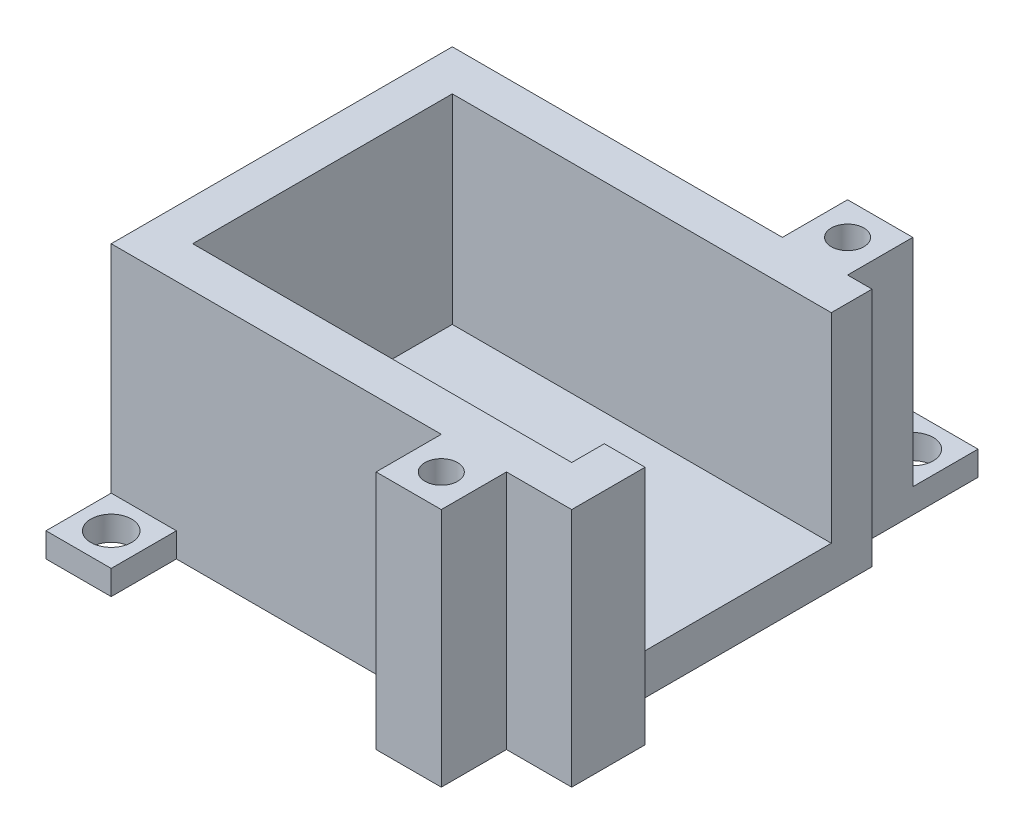
SolidWorks part; units mm, degrees
ref_plane "Front Plane" through (0, 0, 0) normal (0, 0, 1) x (1, 0, 0)
ref_plane "Top Plane" through (0, 0, 0) normal (0, 1, 0) x (1, 0, 0)
ref_plane "Right Plane" through (0, 0, 0) normal (1, 0, 0) x (0, 0, -1)
sketch "Sketch1" plane through (0, 0, 0) normal (0, 1, 0) x (1, 0, 0)
  line L17 (0, 0) -> (51.5, 0)
  line L18 (51.5, 0) -> (51.5, -5)
  line L19 (51.5, -5) -> (5, -5)
  line L20 (5, -5) -> (5, -36.85)
  line L21 (5, -36.85) -> (51.5, -36.85)
  line L22 (51.5, -36.85) -> (51.5, -32.85)
  line L23 (51.5, -32.85) -> (56.5, -32.85)
  line L24 (56.5, -32.85) -> (56.5, -41.85)
  line L25 (56.5, -41.85) -> (0, -41.85)
  line L26 (0, -41.85) -> (0, 0)
  dimension "D1" = 31.85
  dimension "D2" = 5
  dimension "D3" = 5
  dimension "D4" = 5
  dimension "D5" = 5
  dimension "D6" = 51.5
  dimension "D7" = 56.5
  dimension "D8" = 4
extrude "Boss-Extrude1" add sketch "Sketch1" along normal blind 24.5
sketch "Sketch2" plane through (0, 0, 0) normal (0, -1, 0) x (1, 0, 0)
  line L1 (0, 41.85) -> (103, 41.85)
  line L2 (0, 41.85) -> (0, 0)
  line L3 (0, 0) -> (103, 0)
  line L4 (103, 41.85) -> (103, 0)
  dimension "D1" = 103
extrude "Boss-Extrude2" add sketch "Sketch2" along normal blind 5
sketch "Sketch3" plane through (0, 0, 0) normal (0, 1, 0) x (1, 0, 0)
  line L0 (56.5, -32.85) -> (51.5, -32.85) construction
  line L1 (51.5, -5) -> (98, -5)
  line L2 (51.5, -5) -> (51.5, -32.85)
  line L3 (51.5, -32.85) -> (98, -32.85)
  line L4 (98, -5) -> (98, -32.85)
  line L6 (103, 0) -> (103, -41.85) construction
  dimension "D1" = 0
  dimension "D2" = 5
extrude "Cut-Extrude1" cut sketch "Sketch3" against normal blind 26
sketch "Sketch4" plane through (0, 0, 41.85) normal (0, 0, 1) x (1, 0, 0)
  line L1 (0, -5) -> (8, -5)
  line L2 (0, -5) -> (0, -2)
  line L3 (0, -2) -> (8, -2)
  line L4 (8, -5) -> (8, -2)
  dimension "D1" = 3
  dimension "D2" = 8
sketch "Sketch7" plane through (0, 0, 41.85) normal (0, 0, 1) x (1, 0, 0)
  line L1 (0, -2) -> (8, -2)
  line L2 (0, -2) -> (0, -5)
  line L3 (0, -5) -> (8, -5)
  line L4 (8, -2) -> (8, -5)
extrude "Boss-Extrude3" add sketch "Sketch7" along normal blind 8
sketch "Sketch8" plane through (0, -2, 0) normal (0, 1, 0) x (1, 0, 0)
  line L0 (8, -49.85) -> (8, -41.85) construction
  line L1 (0, -41.85) -> (8, -41.85) construction
  circle A0 centre (4, -45.85) radius 2.5
  dimension "D1" = 5
  dimension "D2" = 4
  dimension "D3" = 4
extrude "Cut-Extrude2" cut sketch "Sketch8" against normal blind 8
sketch "Sketch9" plane through (0, 0, 0) normal (0, 0, -1) x (-1, 0, 0)
  line L1 (-103, -5) -> (-95, -5)
  line L2 (-103, -5) -> (-103, -2)
  line L3 (-103, -2) -> (-95, -2)
  line L4 (-95, -5) -> (-95, -2)
  dimension "D1" = 3
  dimension "D2" = 8
extrude "Boss-Extrude4" add sketch "Sketch9" along normal blind 8
sketch "Sketch10" plane through (0, -2, 0) normal (0, 1, 0) x (1, 0, 0)
  line L0 (103, 8) -> (103, 0) construction
  line L1 (95, 8) -> (103, 8) construction
  circle A0 centre (99, 3.9967) radius 2.5
  dimension "D1" = 5
  dimension "D2" = 4
  dimension "D3" = 4.0033
extrude "Cut-Extrude3" cut sketch "Sketch10" against normal blind 8
sketch "Sketch12" plane through (0, 0, 0) normal (0, 1, 0) x (1, 0, 0)
  line L0 (98, -5) -> (51.5, -5) construction
  line L1 (95, -5) -> (83.5, -5)
  line L2 (95, -5) -> (95, 0)
  line L3 (95, 0) -> (83.5, 0)
  line L4 (83.5, -5) -> (83.5, 0)
  line L5 (51.5, 0) -> (103, 0) construction
  line L6 (95, 8) -> (95, 0) construction
  line L7 (51.5, -5) -> (51.5, 0) construction
  dimension "D1" = 0
  dimension "D2" = 32
extrude "Cut-Extrude4" cut sketch "Sketch12" against normal blind 8
sketch "Sketch14" plane through (0, 0, 0) normal (0, 0, -1) x (-1, 0, 0)
  line L1 (-83.5, -5) -> (-75.5, -5)
  line L2 (-83.5, -5) -> (-83.5, -2)
  line L3 (-83.5, -2) -> (-75.5, -2)
  line L4 (-75.5, -5) -> (-75.5, -2)
  dimension "D1" = 8
  dimension "D2" = 3
extrude "Boss-Extrude5" add sketch "Sketch14" along normal blind 8
sketch "Sketch15" plane through (0, -2, 0) normal (0, 1, 0) x (1, 0, 0)
  line L0 (75.5, 8) -> (83.5, 8) construction
  line L1 (83.5, 8) -> (83.5, 0) construction
  circle A0 centre (79.5, 4) radius 2.5
  dimension "D1" = 5
  dimension "D2" = 4
  dimension "D3" = 4
extrude "Cut-Extrude5" cut sketch "Sketch15" against normal blind 8
sketch "Sketch16" plane through (0, 0, 0) normal (0, 0, -1) x (-1, 0, 0)
  line L12 (-51.5, 24.5) -> (0, 24.5) construction
  line L17 (-48.5, 24.5) -> (-40.5, 24.5)
  line L18 (-48.5, 24.5) -> (-48.5, -5)
  line L19 (-48.5, -5) -> (-40.5, -5)
  line L20 (-40.5, 24.5) -> (-40.5, -5)
  line L21 (0, -5) -> (-75.5, -5) construction
  line L22 (-51.5, 24.5) -> (-51.5, 0) construction
  dimension "D1" = 8
  dimension "D2" = 3
extrude "Boss-Extrude6" add sketch "Sketch16" along normal blind 8
sketch "Sketch17" plane through (0, 0, 41.85) normal (0, 0, 1) x (1, 0, 0)
  line L0 (0, 24.5) -> (56.5, 24.5) construction
  line L1 (48.5, 24.5) -> (40.5, 24.5)
  line L2 (48.5, 24.5) -> (48.5, -5)
  line L3 (48.5, -5) -> (40.5, -5)
  line L4 (40.5, 24.5) -> (40.5, -5)
  line L5 (103, -5) -> (8, -5) construction
  line L6 (56.5, 24.5) -> (56.5, 0) construction
  dimension "D1" = 8
  dimension "D2" = 8
extrude "Boss-Extrude7" add sketch "Sketch17" along normal blind 8
sketch "Sketch18" plane through (0, 24.5, 0) normal (0, 1, 0) x (1, 0, 0)
  line L0 (48.5, 8) -> (48.5, 0) construction
  line L2 (40.5, 8) -> (48.5, 8) construction
  line L3 (48.5, -49.85) -> (48.5, -41.85) construction
  line L4 (48.5, -49.85) -> (40.5, -49.85) construction
  circle A0 centre (44.5, 4) radius 2
  circle A1 centre (44.5, -45.85) radius 2
  dimension "D5" = 4
  dimension "D6" = 4
  dimension "D1" = 4
  dimension "D2" = 4
  dimension "D3" = 4
  dimension "D4" = 4
extrude "Cut-Extrude6" cut sketch "Sketch18" against normal blind 10
ref_plane "Plane1" through (40.5, -5, -8) normal (0, 1, 0) x (1, 0, 0)
sketch "Sketch20" plane through (0, 0, -8) normal (0, 0, -1) x (-1, 0, 0)
  line L0 (-48.5, 24.5) -> (-48.5, -5) construction
  line L1 (-40.5, -5) -> (-48.5, -5)
  line L2 (-40.5, -5) -> (-40.5, -2)
  line L3 (-40.5, -2) -> (-48.5, -2)
  line L4 (-48.5, -5) -> (-48.5, -2)
  dimension "D1" = 3
extrude "Boss-Extrude8" add sketch "Sketch20" along normal blind 8
sketch "Sketch21" plane through (0, -2, 0) normal (0, 1, 0) x (1, 0, 0)
  line L0 (40.5, 16) -> (48.5, 16) construction
  line L1 (48.5, 16) -> (48.5, 8) construction
  circle A0 centre (44.5, 12) radius 2.5
  dimension "D1" = 5
  dimension "D2" = 4
  dimension "D3" = 4
extrude "Cut-Extrude7" cut sketch "Sketch21" against normal blind 8
sketch "Sketch22" plane through (0, 0, 0) normal (0, 1, 0) x (1, 0, 0)
  line L0 (83.5, -5) -> (51.5, -5) construction
  line L1 (103, 8) -> (56.5, 8)
  line L2 (103, 8) -> (103, -41.85)
  line L3 (103, -41.85) -> (56.5, -41.85)
  line L4 (56.5, 8) -> (56.5, -41.85)
  line L5 (51.5, 0) -> (56.5, 0)
  line L6 (51.5, 0) -> (51.5, -5)
  line L7 (51.5, -5) -> (56.5, -5)
  line L8 (56.5, 0) -> (56.5, -5)
  line M5 (51.5, -5) -> (83.5, -5)
  line M6 (83.5, -5) -> (83.5, 0)
  line M7 (83.5, 0) -> (51.5, 0)
  line M8 (51.5, 0) -> (51.5, -5)
extrude "Cut-Extrude8" cut sketch "Sketch22" against normal blind 8 contours L1 L4 L3 L2 M7 M6 M5 | L4 M7 M8 M5
sketch "Sketch23" plane through (0, 0, 0) normal (0, 1, 0) x (1, 0, 0)
  line L1 (56.5, 0) -> (83.5, 0)
  line L2 (56.5, 0) -> (56.5, -5)
  line L3 (56.5, -5) -> (83.5, -5)
  line L4 (83.5, 0) -> (83.5, -5)
extrude "Cut-Extrude9" cut sketch "Sketch23" against normal blind 8
